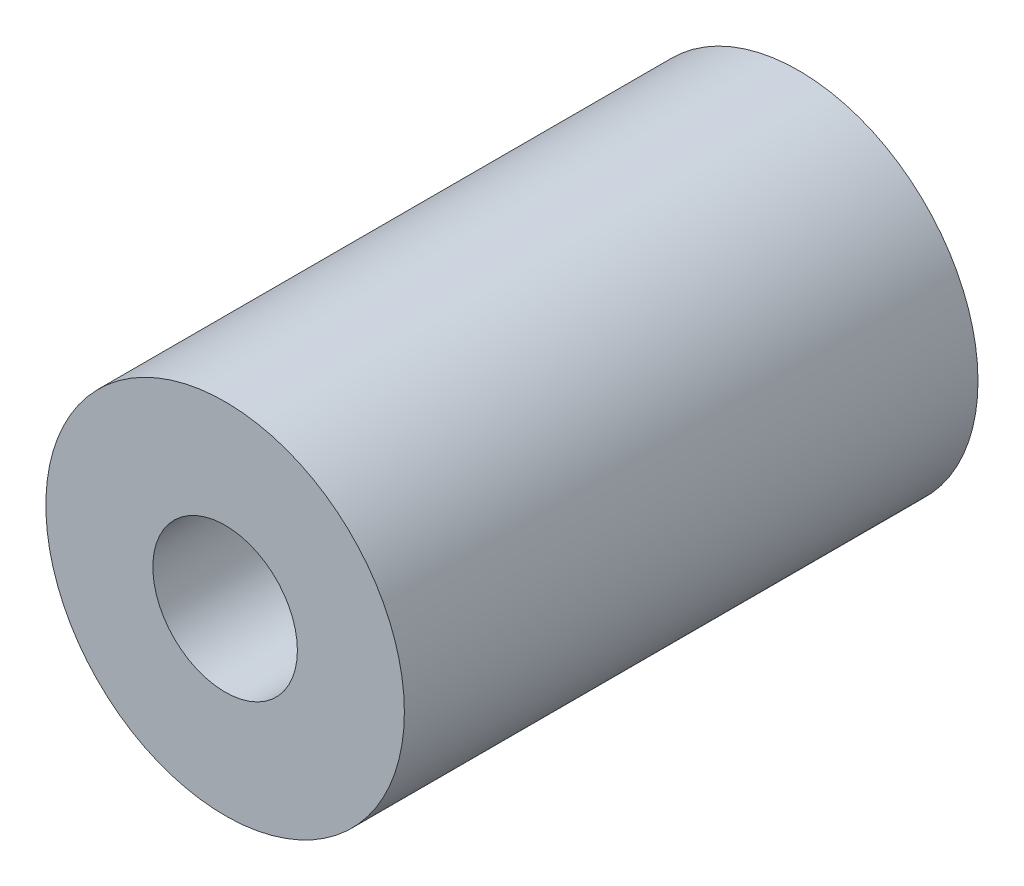
SolidWorks part; units mm, degrees
ref_plane "Front Plane" through (0, 0, 0) normal (0, 0, 1) x (1, 0, 0)
ref_plane "Top Plane" through (0, 0, 0) normal (0, 1, 0) x (1, 0, 0)
ref_plane "Right Plane" through (0, 0, 0) normal (1, 0, 0) x (0, 0, -1)
sketch "Sketch1" plane through (0, 0, 0) normal (0, 0, 1) x (1, 0, 0)
  circle A0 centre (0, 0) radius 7.9375
  circle A1 centre (0, 0) radius 3.2004
  dimension "OD" = 15.875
  dimension "ID" = 6.4008
extrude "Extrude1" add sketch "Sketch1" along normal mid plane 25.4
sketch "Sketch2" plane through (0, 0, 0) normal (1, 0, 0) x (0, 0, -1)
  line L0 (-12.7, -3.2004) -> (12.7, -3.2004) construction
  line L3 (12.7, 3.2004) -> (-12.7, 3.2004) construction
  line L5 (-12.7, -3.2004) -> (12.7, -3.2004)
  line L6 (12.7, 3.2004) -> (-12.7, 3.2004)
sketch "Sketch4" plane through (0, 0, 12.7) normal (0, 0, 1) x (1, 0, 0)
  line L0 (0, 0) -> (-2.263, 2.263)
  line L1 (0, -8.7312) -> (0, 8.7312) construction
  circle A0 centre (0, 0) radius 3.2004 construction
  dimension "D1" = 45
